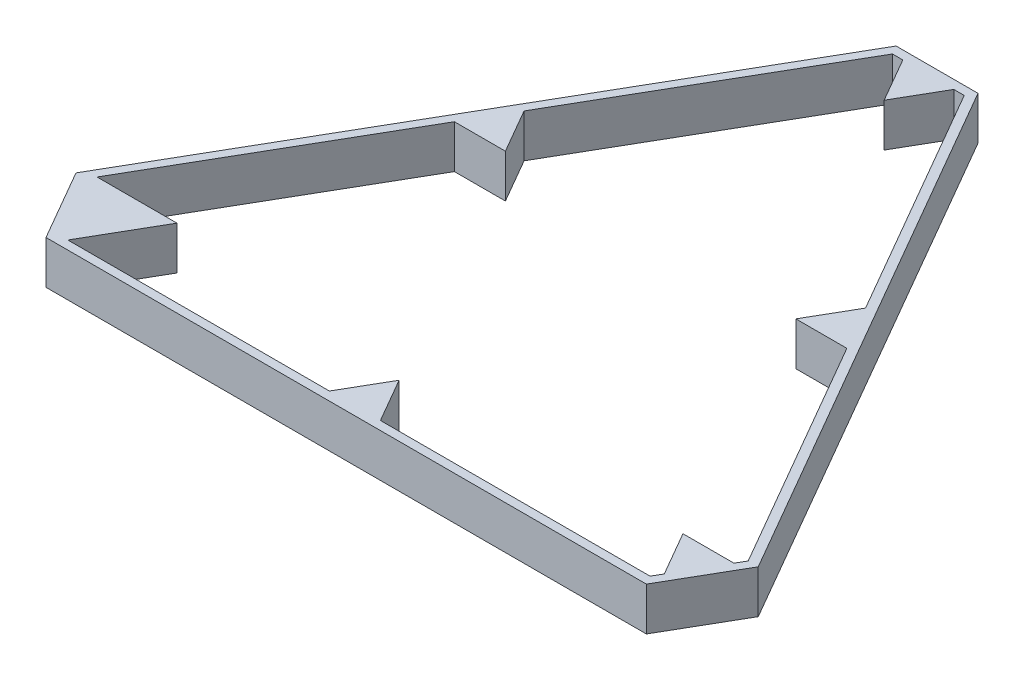
SolidWorks part; units mm, degrees
ref_plane "Front Plane" through (0, 0, 0) normal (0, 0, 1) x (1, 0, 0)
ref_plane "Top Plane" through (0, 0, 0) normal (0, 1, 0) x (1, 0, 0)
ref_plane "Right Plane" through (0, 0, 0) normal (1, 0, 0) x (0, 0, -1)
sketch "Sketch1" plane through (0, 0, 0) normal (0, 1, 0) x (1, 0, 0)
  line L17 (-84.5662, 18.8923) -> (-84.5662, 18.3923) construction
  line L24 (-89.7106, 9.9821) -> (-89.2776, 10.2321) construction
  line L25 (-79.4219, 9.9821) -> (-79.8549, 10.2321) construction
  line L26 (-93.9889, 18.3923) -> (-84.5662, 2.0718)
  line L27 (-84.5662, 2.0718) -> (-75.1436, 18.3923)
  line L28 (-93.9889, 18.3923) -> (-75.1436, 18.3923)
  line L29 (-2.5, 5.4019) -> (-2.067, 5.1519) construction
  line L58 (2.5, 5.4019) -> (2.067, 5.1519) construction
  line L59 (0, 1.0718) -> (0, 1.5718) construction
  line L65 (-4.134, 1.5718) -> (4.134, 1.5718)
  line L66 (-11.7321, 167.8653) -> (11.7321, 167.8653)
  line L67 (97.7417, 18.8923) -> (86.0096, -1.4282)
  line L68 (97.7417, 18.8923) -> (11.7321, 167.8653)
  line L69 (0, 8.7321) -> (4.134, 1.5718)
  line L71 (-4.134, 1.5718) -> (0, 8.7321)
  line L72 (-97.7417, 18.8923) -> (-86.0096, -1.4282)
  line L73 (-86.0096, -1.4282) -> (86.0096, -1.4282)
  line L74 (-97.7417, 18.8923) -> (-11.7321, 167.8653)
  line L79 (87.2106, 14.3122) -> (87.2106, 13.8122) construction
  line L81 (84.7106, 9.9821) -> (85.1436, 10.2321) construction
  line L97 (-94.8549, 18.8923) -> (-84.5662, 1.0718)
  line L100 (-94.8549, 18.8923) -> (-74.2776, 18.8923)
  line L106 (-84.5662, 1.0718) -> (-74.2776, 18.8923)
  line L108 (50.0718, 96.4589) -> (55.0718, 87.7987)
  line L109 (41.6077, 85.7987) -> (56.2265, 85.7987)
  line L111 (50.0718, 96.4589) -> (45.0718, 87.7987)
  line L112 (45.0718, 87.7987) -> (55.0718, 87.7987)
  line L115 (56.2265, 85.7987) -> (94.8549, 18.8923)
  line L116 (48.9171, 98.4589) -> (10.2887, 165.3653)
  line L117 (41.6077, 85.7987) -> (48.9171, 98.4589)
  line L118 (-5, 165.3653) -> (5, 165.3653)
  line L121 (-55.0718, 87.7987) -> (-50.0718, 96.4589)
  line L122 (-5, 165.3653) -> (0, 156.7051)
  line L123 (5, 165.3653) -> (0, 156.7051)
  line L125 (0, 152.7051) -> (7.3094, 165.3653)
  line L126 (0, 152.7051) -> (-7.3094, 165.3653)
  line L127 (-10.2887, 165.3653) -> (-7.3094, 165.3653)
  line L128 (7.3094, 165.3653) -> (10.2887, 165.3653)
  line L129 (-50.0718, 96.4589) -> (-45.0718, 87.7987)
  line L130 (-55.0718, 87.7987) -> (-45.0718, 87.7987)
  line L131 (-48.9171, 98.4589) -> (-10.2887, 165.3653)
  line L132 (-41.6077, 85.7987) -> (-48.9171, 98.4589)
  line L133 (-41.6077, 85.7987) -> (-56.2265, 85.7987)
  line L134 (5, 1.0718) -> (-5, 1.0718)
  line L135 (89.7106, 9.9821) -> (89.2776, 10.2321) construction
  line L136 (-5, 1.0718) -> (0, 9.7321)
  line L137 (0, 9.7321) -> (5, 1.0718)
  line L138 (83.0766, 13.8122) -> (91.3446, 13.8122)
  line L139 (0, 13.7321) -> (-7.3094, 1.0718)
  line L143 (84.5662, 1.0718) -> (7.3094, 1.0718)
  line L144 (0, 13.7321) -> (7.3094, 1.0718)
  line L145 (92.2106, 14.3122) -> (87.2106, 5.6519)
  line L146 (87.2106, 6.6519) -> (91.3446, 13.8122)
  line L147 (87.2106, 5.6519) -> (82.2106, 14.3122)
  line L148 (82.2106, 14.3122) -> (92.2106, 14.3122)
  line L149 (83.0766, 13.8122) -> (87.2106, 6.6519)
  line L150 (94.8549, 18.8923) -> (93.3653, 16.3122)
  line L151 (78.7465, 16.3122) -> (86.0559, 3.6519)
  line L152 (78.7465, 16.3122) -> (93.3653, 16.3122)
  line L153 (86.0559, 3.6519) -> (84.5662, 1.0718)
  line L154 (-82.2568, 1.0718) -> (-7.3094, 1.0718)
  line L155 (-93.7002, 20.8923) -> (-56.2265, 85.7987)
  line L156 (-70.8135, 20.8923) -> (-93.7002, 20.8923)
  line L157 (47.5718, 92.1288) -> (48.0048, 91.8788) construction
  line L158 (52.5718, 92.1288) -> (52.1388, 91.8788) construction
  line L159 (-70.8135, 20.8923) -> (-82.2568, 1.0718)
  line L160 (50.0718, 87.7987) -> (50.0718, 88.2987) construction
  line L161 (45.9378, 88.2987) -> (54.2058, 88.2987)
  line L162 (50.0718, 95.4589) -> (54.2058, 88.2987)
  line L163 (45.9378, 88.2987) -> (50.0718, 95.4589)
  line L164 (0, 165.3653) -> (0, 164.8653) construction
  line L165 (-2.5, 161.0352) -> (-2.067, 161.2852) construction
  line L166 (2.5, 161.0352) -> (2.067, 161.2852) construction
  line L167 (-4.134, 164.8653) -> (4.134, 164.8653)
  line L168 (0, 157.7051) -> (4.134, 164.8653)
  line L169 (-4.134, 164.8653) -> (0, 157.7051)
  line L170 (-52.5718, 92.1288) -> (-52.1388, 91.8788) construction
  line L171 (-47.5718, 92.1288) -> (-48.0048, 91.8788) construction
  line L172 (-50.0718, 87.7987) -> (-50.0718, 88.2987) construction
  line L173 (-54.2058, 88.2987) -> (-45.9378, 88.2987)
  line L174 (-50.0718, 95.4589) -> (-45.9378, 88.2987)
  line L175 (-54.2058, 88.2987) -> (-50.0718, 95.4589)
  point P9 (-89.2776, 10.2321)
  point P12 (-79.8549, 10.2321)
  point P15 (-84.5662, 18.3923)
  point P21 (0, 1.5718)
  point P24 (2.067, 5.1519)
  point P27 (-2.067, 5.1519)
  point P32 (87.2106, 13.8122)
  point P36 (89.2776, 10.2321)
  point P41 (85.1436, 10.2321)
  point P48 (50.0718, 88.2987)
  point P51 (50.0718, 88.2987)
  point P54 (52.1388, 91.8788)
  point P58 (48.0048, 91.8788)
  point P74 (0, 164.8653)
  point P89 (2.067, 161.2852)
  point P97 (-2.067, 161.2852)
  point P106 (-50.0718, 88.2987)
  point P109 (-50.0718, 88.2987)
  point P114 (-48.0048, 91.8788)
  point P119 (-52.1388, 91.8788)
extrude "Boss-Extrude1" add sketch "Sketch1" along normal blind 12.38
